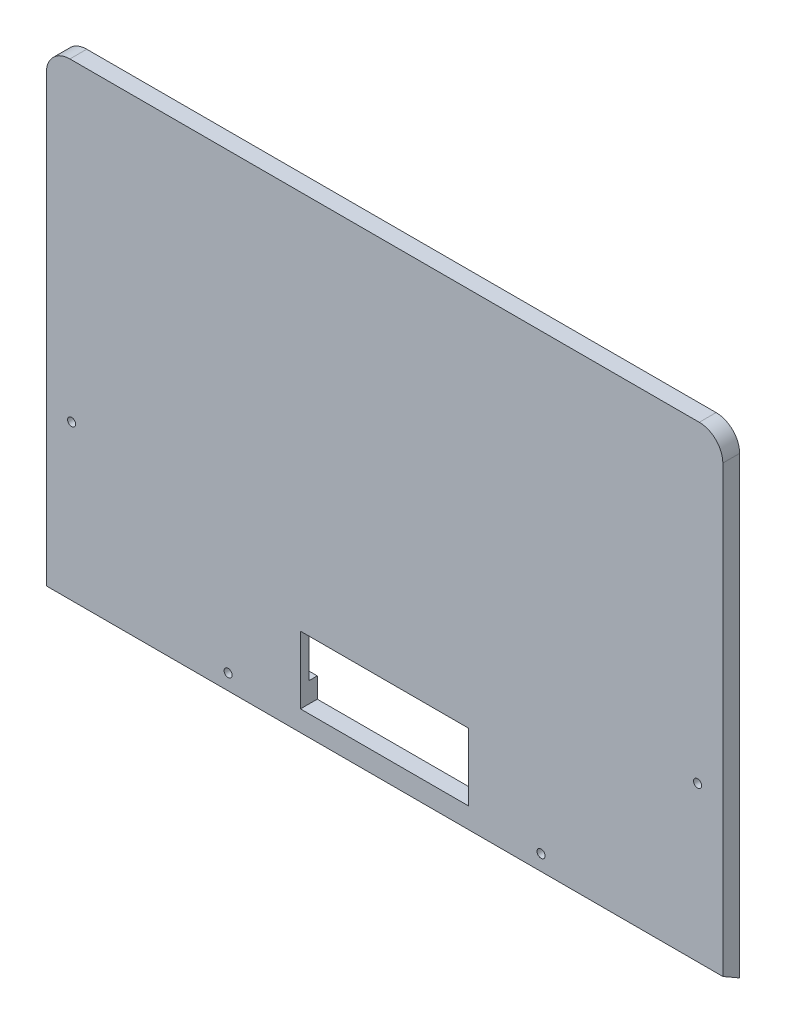
SolidWorks part; units mm, degrees
ref_plane "前视基准面" through (0, 0, 0) normal (0, 0, 1) x (1, 0, 0)
ref_plane "上视基准面" through (0, 0, 0) normal (0, 1, 0) x (1, 0, 0)
ref_plane "右视基准面" through (0, 0, 0) normal (1, 0, 0) x (0, 0, -1)
other "Configuration Table"
sketch "草图3" plane through (0, 0, 0) normal (0, 0, 1) x (1, 0, 0)
  line L1 (-85.5, -56) -> (85.5, -56) construction
  line L2 (-85.5, -56) -> (-85.5, 56) construction
  line L3 (-85.5, 56) -> (85.5, 56) construction
  line L4 (85.5, -56) -> (85.5, 56) construction
  line L5 (-85.5, -56) -> (85.5, 56) construction
  line L6 (-85.5, 56) -> (85.5, -56) construction
  line L7 (-100.5, 71) -> (100.5, 71)
  line L8 (-100.5, 71) -> (-100.5, -71)
  line L9 (-100.5, -71) -> (100.5, -71)
  line L10 (100.5, 71) -> (100.5, -71)
  line L11 (-100.5, 71) -> (100.5, -71) construction
  line L12 (-100.5, -71) -> (100.5, 71) construction
  point P0 (0, 0)
  point P6 (0, 0)
  dimension "D1" = 112
  dimension "D2" = 171
  dimension "D3" = 142
  dimension "D4" = 201
extrude "凸台-拉伸2" add sketch "草图3" along normal blind 5
sketch "草图4" plane through (0, 0, 0) normal (0, 0, 1) x (1, 0, 0)
  line L1 (-85.5, 56) -> (85.5, 56)
  line L2 (-85.5, 56) -> (-85.5, -56)
  line L3 (-85.5, -56) -> (85.5, -56)
  line L4 (85.5, 56) -> (85.5, -56)
  line L5 (-85.5, 56) -> (85.5, -56) construction
  line L6 (-85.5, -56) -> (85.5, 56) construction
  point P0 (0, 0)
  dimension "D1" = 112
  dimension "D2" = 171
extrude "切除-拉伸1" cut sketch "草图4" along normal blind 2.5
sketch "草图5" plane through (0, 0, 0) normal (0, 0, 1) x (1, 0, 0)
  line L0 (0, 0) -> (0, -52) construction
  line L2 (-25, -62) -> (25, -62)
  line L3 (-25, -62) -> (-25, -42)
  line L4 (-25, -42) -> (25, -42)
  line L5 (25, -62) -> (25, -42)
  line L6 (-25, -62) -> (25, -42) construction
  line L7 (-25, -42) -> (25, -62) construction
  dimension "D1" = 52
  dimension "D2" = 50
  dimension "D3" = 20
extrude "切除-拉伸6" cut sketch "草图5" along normal blind 15
ref_plane "基准面2" through (0, 0, 0) normal (0, 0, -1) x (-1, 0, 0)
sketch "草图6" plane through (0, 0, 0) normal (0, 0, -1) x (-1, 0, 0)
  line L0 (-100.5, 71) -> (-85.5, 56) construction
  line L1 (-85.5, -56) -> (-100.5, -71) construction
  line L2 (85.5, 56) -> (100.5, 71) construction
  line L3 (85.5, -56) -> (100.5, -71) construction
  circle A0 centre (-93, 63.5) radius 1.2
  circle A1 centre (93, 63.5) radius 1.2
  circle A2 centre (93, -63.5) radius 1.2
  circle A3 centre (-93, -63.5) radius 1.2
  dimension "D1" = 2.4
  dimension "D2" = 2
  dimension "D3" = 2
extrude "切除-拉伸7" cut sketch "草图6" against normal blind 3
ref_plane "基准面3" through (-100.5, 0, 0) normal (-1, 0, 0) x (0, 0, 1)
sketch "草图9" plane through (-100.5, 0, 0) normal (-1, 0, 0) x (0, 0, 1)
  line L0 (0, -71) -> (5, -71)
  line L1 (5, -71) -> (5, -68.1132)
  line L2 (5, 71) -> (5, -71) construction
  line L3 (5, -68.1132) -> (0, -71)
  dimension "D1" = 30
extrude "切除-拉伸8" cut sketch "草图9" against normal up to next
sketch "草图11" plane through (0, 0, 0) normal (0, 0, -1) x (-1, 0, 0)
  line L0 (46.5, -63.5) -> (46.5, -58.6101) construction
  line L1 (0, -63.5) -> (93, -63.5) construction
  line L2 (0, -63.5) -> (-93, -63.5) construction
  line L3 (-46.5, -63.5) -> (-46.5, -58.6101) construction
  line L4 (93, -63.5) -> (93, -22.1704) construction
  line L5 (93, -22.1704) -> (-93, -22.1704) construction
  line L6 (-93, -22.1704) -> (-93, -63.5) construction
hole_wizard "打孔尺寸(%根据十字)槽沉头自攻螺钉的类型1" positions "草图12" profile "草图13" countersink size "ST2.2" standard "GB" end condition up to next
sketch "草图12" plane through (0, 0, 0) normal (0, 0, -1) x (-1, 0, 0)
  point P0 (-93, -22.1704)
  point P3 (-46.5, -63.5)
  point P6 (46.5, -63.5)
  point P9 (93, -22.1704)
sketch "草图13" plane through (93, -22.1704, 0) normal (1, 0, 0) x (0, 1, 0)
  line L0 (0, 0) -> (0, 5)
  line L1 (0, 5) -> (1.2, 5)
  line L2 (1.2, 5) -> (1.2, 1.05)
  line L3 (1.2, 1.05) -> (2.25, 0)
  line L5 (2.25, 0) -> (0, 0)
  line L6 (-1.2, 1.05) -> (-2.25, 0) construction
  line L11 (0, -6.35) -> (0, 107.95) construction
  dimension "通孔孔直径" = 2.4
  dimension "通孔孔深度" = 5
  dimension "近端锥形沉头孔直径" = 4.5
  dimension "近端锥形沉头孔角度" = 90
ref_plane "基准面4" through (0, 0, 5) normal (0, 0, 1) x (1, 0, 0)
sketch "草图14" plane through (0, 0, 5) normal (0, 0, 1) x (1, 0, 0)
  line L0 (-93, -22.1704) -> (-93, -63.5) construction
  line L1 (-93, -63.5) -> (-46.5, -63.5) construction
  line L2 (-46.5, -63.5) -> (46.5, -63.5) construction
  line L3 (46.5, -63.5) -> (93, -63.5) construction
  line L4 (93, -63.5) -> (93, -22.1704) construction
  line L5 (93, -22.1704) -> (-93, -22.1704) construction
  line L6 (-100.5, -68.1132) -> (-100.5, -12.192) construction
  line L7 (-100.5, 71) -> (-100.5, -68.1132) construction
  line L8 (-100.5, -12.192) -> (100.5, -12.192) construction
  line L9 (100.5, -68.1132) -> (100.5, 71) construction
  line L10 (100.5, -12.192) -> (100.5, -68.1132) construction
  line L11 (100.5, -68.1132) -> (-100.5, -68.1132) construction
fillet "圆角1" radius 7 2 edges at (100.5, 71, 2.5) (-100.5, 71, 2.5)
